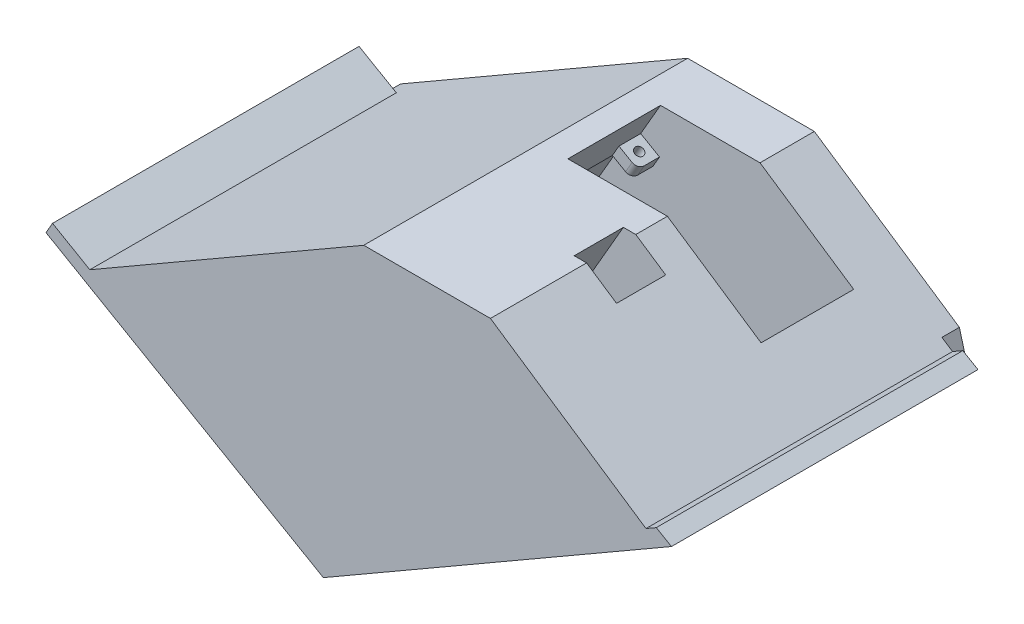
SolidWorks part; units mm, degrees
material "ABS"
ref_plane "前基準面" through (0, 0, 0) normal (0, 0, 1) x (1, 0, 0)
ref_plane "上基準面" through (0, 0, 0) normal (0, 1, 0) x (1, 0, 0)
ref_plane "右基準面" through (0, 0, 0) normal (1, 0, 0) x (0, 0, -1)
sketch "草圖1" plane through (0, 0, 0) normal (0, 0, 1) x (1, 0, 0)
  line L0 (-93.526, -88.0487) -> (-102.1061, -83.095)
  line L3 (-102.1061, -83.095) -> (-103.6061, -85.6931)
  line L4 (-103.6061, -85.6931) -> (-97.5195, -89.2072)
  line L5 (-97.5195, -89.2072) -> (-39.8137, -122.5236)
  line L6 (-39.8137, -122.5236) -> (36.1415, -78.6709)
  line L7 (36.1415, -78.6709) -> (40.2575, -76.2945)
  line L8 (40.2575, -76.2945) -> (36.7575, -74.2738)
  line L9 (36.7575, -74.2738) -> (34.3915, -75.6398)
  line L11 (34.3915, -75.6398) -> (-1.3835, -51.6757)
  line L12 (-1.3835, -51.6757) -> (-30.526, -51.6757)
  line L15 (-30.526, -51.6757) -> (-93.526, -88.0487)
  point P5 (0, 0)
  point P29 (0, 0)
  point P30 (0, 0)
  point P32 (0, 0)
  point P33 (0, 0)
  point P34 (0, 0)
  point P35 (0, 0)
  point P38 (0, 0)
extrude "填料-伸長1" add sketch "草圖1" along normal blind 74.5 contours L15 L0 L3 L4 L5 L6 L7 L8 L9 L11 L12
sketch "草圖2" plane through (0, 0, 0) normal (0, 0, -1) x (-1, 0, 0)
  line L0 (-40.2575, -76.2945) -> (-36.7575, -74.2738)
  line L1 (-36.7575, -74.2738) -> (-34.3915, -75.6398)
  line L2 (-34.3915, -75.6398) -> (-37.8915, -77.6605)
  line L3 (39.8137, -122.5236) -> (-40.2575, -76.2945) construction
  line L4 (-37.8915, -77.6605) -> (-40.2575, -76.2945)
  line L5 (102.1061, -83.095) -> (93.526, -88.0487)
  line L6 (93.526, -88.0487) -> (96.526, -89.7808)
  line L7 (103.6061, -85.6931) -> (39.8137, -122.5236) construction
  line L8 (96.526, -89.7808) -> (103.6061, -85.6931)
  line L9 (103.6061, -85.6931) -> (102.1061, -83.095)
extrude "除料-伸長1" cut sketch "草圖2" against normal blind 4
sketch "草圖3" plane through (0, 0, 0) normal (0, 0, -1) x (-1, 0, 0)
  line L0 (-33.6354, -80.1178) -> (-31.971, -74.0184)
  line L1 (-34.3915, -75.6398) -> (1.3835, -51.6757) construction
  line L2 (-31.971, -74.0184) -> (-37.8915, -77.6605)
  line L3 (-37.8915, -77.6605) -> (-33.6354, -80.1178)
  line L5 (39.8137, -122.5236) -> (-37.8915, -77.6605) construction
extrude "除料-伸長2" cut sketch "草圖3" against normal blind 4
sketch "草圖4" plane through (0, 0, 74.5) normal (0, 0, 1) x (1, 0, 0)
  line L0 (-60.2173, -110.7436) -> (-31.7133, -61.3734)
  line L1 (-103.6061, -85.6931) -> (-39.8137, -122.5236) construction
  line L2 (-31.7133, -61.3734) -> (12.1941, -86.7234)
  line L3 (12.1941, -86.7234) -> (7.1941, -95.3836)
  line L4 (-39.8137, -122.5236) -> (40.2575, -76.2945) construction
  line L5 (7.1941, -95.3836) -> (-39.8137, -122.5236)
  line L6 (-39.8137, -122.5236) -> (-60.2173, -110.7436)
  point P4 (-109.9774, -30.9242)
  point P11 (-55.478, -82.4705)
  point P12 (0, 0)
  point P13 (-5.5822, -95.111)
  point P14 (0, 0)
  point P15 (-39.8137, -87.5146)
  point P16 (-6.7767, -98.8895)
  point P17 (-50.7201, -84.464)
  point P18 (-36.5485, -92.0736)
  dimension "D1" = 90
  dimension "D2" = 90
  dimension "D3" = 90
  dimension "D4" = 10
  dimension "D5" = 50.7
  dimension "D6" = 23.56
extrude "除料-伸長3" cut sketch "草圖4" against normal blind 62
sketch "草圖5" plane through (-34.5038, -59.7623, 0) normal (-0.5, -0.866, 0) x (0.866, -0.5, 0)
  line L0 (53.9221, 12.5) -> (3.2221, 12.5) construction
  line L1 (4.8221, 12.5) -> (50.5221, 12.5)
  line L2 (4.8221, 12.5) -> (4.8221, 33.8)
  line L3 (4.8221, 33.8) -> (50.5221, 33.8)
  line L4 (50.5221, 12.5) -> (50.5221, 33.8)
  line L5 (3.2221, 12.5) -> (3.2221, 74.5) construction
  line L7 (50.5221, 12.5) -> (50.5221, 33.8) construction
  dimension "D1" = 21.3
  dimension "D3" = 1.6
  dimension "D4" = 0
extrude "除料-伸長4" cut sketch "草圖5" against normal up to next
sketch "草圖6" plane through (-34.5038, -59.7623, 0) normal (-0.5, -0.866, 0) x (0.866, -0.5, 0)
  line L1 (4.8221, 12.5) -> (9.8221, 12.5)
  line L2 (4.8221, 12.5) -> (4.8221, 17.5)
  line L3 (4.8221, 17.5) -> (9.8221, 17.5)
  line L4 (9.8221, 12.5) -> (9.8221, 17.5)
  line L5 (50.5221, 33.8) -> (45.5221, 33.8)
  line L6 (50.5221, 33.8) -> (50.5221, 28.8)
  line L7 (50.5221, 28.8) -> (45.5221, 28.8)
  line L8 (45.5221, 33.8) -> (45.5221, 28.8)
  circle A0 centre (7.3221, 15) radius 0.9988
  circle A1 centre (48.0221, 31.3) radius 1.4
  circle A2 centre (8.3221, 16) radius 1.5
  circle A3 centre (47.0221, 30.3) radius 1.5
  line M10 (4.8221, 12.5) -> (4.8221, 33.8)
  line M11 (4.8221, 33.8) -> (50.5221, 33.8)
  line M12 (50.5221, 33.8) -> (50.5221, 12.5)
  dimension "D5" = 2.8
  dimension "D6" = 2.5
  dimension "D7" = 2.5
  dimension "D8" = 2.5
  dimension "D9" = 2.5
  dimension "D10" = 3.5
  dimension "D11" = 3.5
  dimension "D12" = 3.5
  dimension "D13" = 3.5
  dimension "D14" = 3
  dimension "D15" = 3
  dimension "D1" = 5
  dimension "D2" = 5
  dimension "D3" = 5
  dimension "D4" = 5
extrude "填料-伸長2" add sketch "草圖6" against normal blind 3 contours A2 A0 | A2 L3 L1 L4 A0 M10 | A3 A1 L7 L8 M12 M11 | A1 A3
sketch "草圖7" plane through (-34.5038, -59.7623, 0) normal (-0.5, -0.866, 0) x (0.866, -0.5, 0)
  line L1 (22.1712, 41.0721) -> (32.9109, 41.0721)
  line L2 (22.1712, 41.0721) -> (22.1712, 52.3843)
  line L3 (22.1712, 52.3843) -> (32.9109, 52.3843)
  line L4 (32.9109, 41.0721) -> (32.9109, 52.3843)
extrude "除料-伸長5" cut sketch "草圖7" against normal up to next
sketch "草圖8" plane through (-34.5038, -59.7623, 0) normal (-0.5, -0.866, 0) x (0.866, -0.5, 0)
  line L0 (22.1712, 52.3843) -> (32.9109, 52.3843)
  line L1 (32.9109, 52.3843) -> (32.9109, 41.0721)
  line L2 (32.9109, 41.0721) -> (53.9221, 41.0721)
  line L3 (53.9221, 12.5) -> (53.9221, 74.5) construction
  line L4 (53.9221, 41.0721) -> (53.9221, 12.5)
  line L5 (53.9221, 12.5) -> (3.2221, 12.5)
  line L6 (3.2221, 12.5) -> (3.2221, 41.0721)
  line L7 (3.2221, 12.5) -> (3.2221, 74.5) construction
  line L8 (3.2221, 41.0721) -> (22.1712, 41.0721)
  line L9 (22.1712, 41.0721) -> (22.1712, 52.3843)
  line M2 (22.1712, 41.0721) -> (22.1712, 52.3843)
  line M3 (22.1712, 52.3843) -> (32.9109, 52.3843)
  line M4 (32.9109, 52.3843) -> (32.9109, 41.0721)
  line M11 (53.9221, 12.5) -> (53.9221, 74.5)
  line M12 (53.9221, 74.5) -> (3.2221, 74.5)
  line M13 (3.2221, 74.5) -> (3.2221, 12.5)
extrude "填料-伸長3" add sketch "草圖8" along normal up to surface (57.0079 mm away) contours L8 L2 M13 M2 M3 M4 M11 M12 up to face at (-75.0408, -102.1853, 22.75)
sketch "草圖9" plane through (0, 0, 0) normal (0, 0, -1) x (-1, 0, 0)
  line L0 (39.8137, -122.5236) -> (16.3098, -136.0936)
  line L1 (16.3098, -136.0936) -> (-7.1941, -95.3836)
  line L2 (39.8137, -122.5236) -> (-33.6354, -80.1178) construction
  line L3 (-7.1941, -95.3836) -> (39.8137, -122.5236)
  line L4 (96.526, -89.7808) -> (39.8137, -122.5236) construction
  line L5 (16.3098, -136.0936) -> (-7.1941, -95.3836) construction
extrude "除料-伸長6" cut sketch "草圖9" against normal up to surface (74.5 mm away) up to face at (-22.8857, -81.7873, 74.5)
